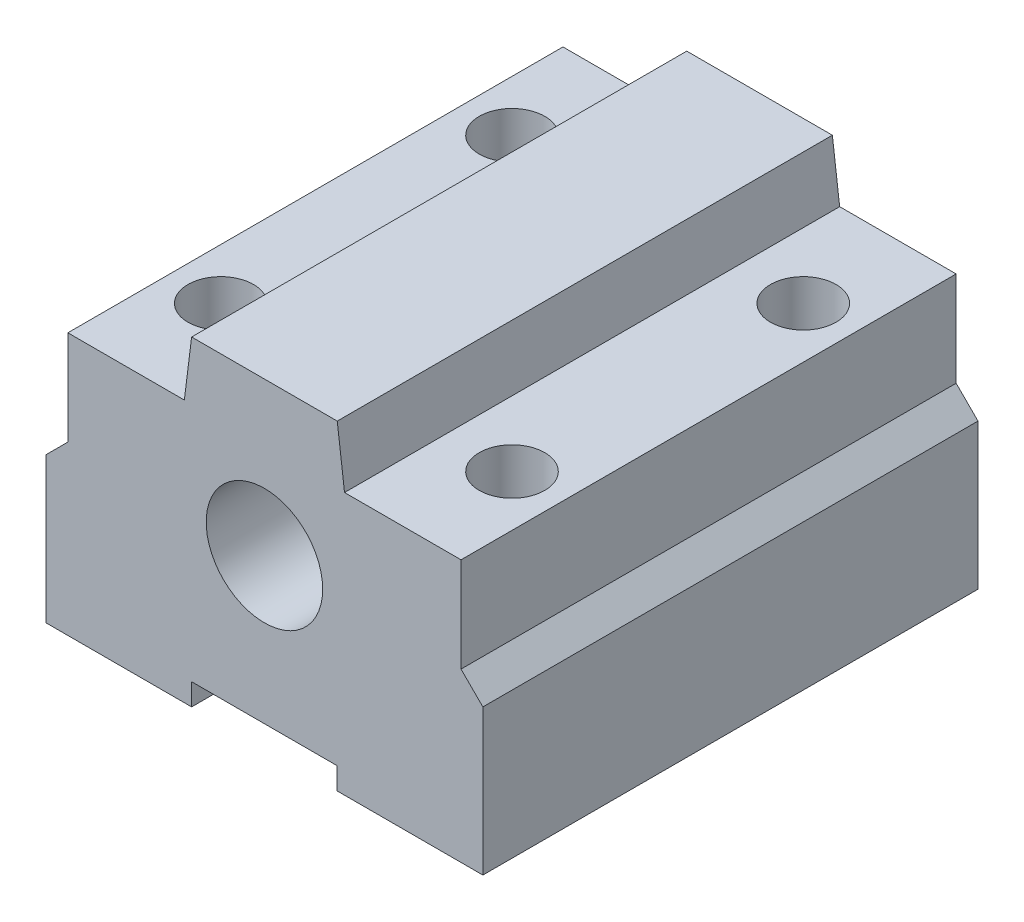
SolidWorks part; units mm, degrees
material "1060 Alloy"
ref_plane "Front Plane" through (0, 0, 0) normal (0, 0, 1) x (1, 0, 0)
ref_plane "Top Plane" through (0, 0, 0) normal (0, 1, 0) x (1, 0, 0)
ref_plane "Right Plane" through (0, 0, 0) normal (1, 0, 0) x (0, 0, -1)
sketch "Sketch1" plane through (0, 0, 0) normal (0, 0, 1) x (1, 0, 0)
  line L0 (5, -10) -> (-5, -10)
  line L1 (5, -10) -> (5, -11.5)
  line L2 (5, -11.5) -> (15, -11.5)
  line L3 (15, -11.5) -> (15, -1.5)
  line L4 (15, -1.5) -> (13.5, 0)
  line L5 (13.5, 0) -> (13.5, 6.5)
  line L6 (5, 10.5) -> (5.5, 6.5)
  line L7 (5, 10.5) -> (-5, 10.5)
  line L8 (0, 10.5) -> (0, -10) construction
  line L9 (5.5, 6.5) -> (13.5, 6.5)
  line L10 (-5, -10) -> (-5, -11.5)
  line L11 (-5, -11.5) -> (-15, -11.5)
  line L12 (-15, -11.5) -> (-15, -1.5)
  line L13 (-15, -1.5) -> (-13.5, 0)
  line L14 (-13.5, 0) -> (-13.5, 6.5)
  line L15 (-5.5, 6.5) -> (-13.5, 6.5)
  line L16 (-5, 10.5) -> (-5.5, 6.5)
  circle A0 centre (0, 0) radius 4
  dimension "D1" = 8
  dimension "D6" = 10
  dimension "D2" = 15
  dimension "D3" = 22
  dimension "D4" = 1.5
  dimension "D5" = 5
  dimension "D7" = 1.5
  dimension "D8" = 10
  dimension "D9" = 5
  dimension "D10" = 8
  dimension "D11" = 1.5
  dimension "D12" = 4
extrude "Boss-Extrude1" add sketch "Sketch1" along normal blind 34
sketch "Sketch2" plane through (0, 6.5, 0) normal (0, 1, 0) x (1, 0, 0)
  line L0 (13.5, 0) -> (5.5, 0) construction
  line L1 (13.5, -34) -> (13.5, 0) construction
  circle A0 centre (10, -27) radius 2.25
  circle A1 centre (10, -7) radius 2.25
  dimension "D1" = 20
  dimension "D2" = 7
  dimension "D3" = 3.5
  dimension "D4" = 4.5
extrude "Cut-Extrude1" cut sketch "Sketch2" against normal through all
mirror "Mirror1" about plane through (0, 0, 0) normal (1, 0, 0) of "Cut-Extrude1"
